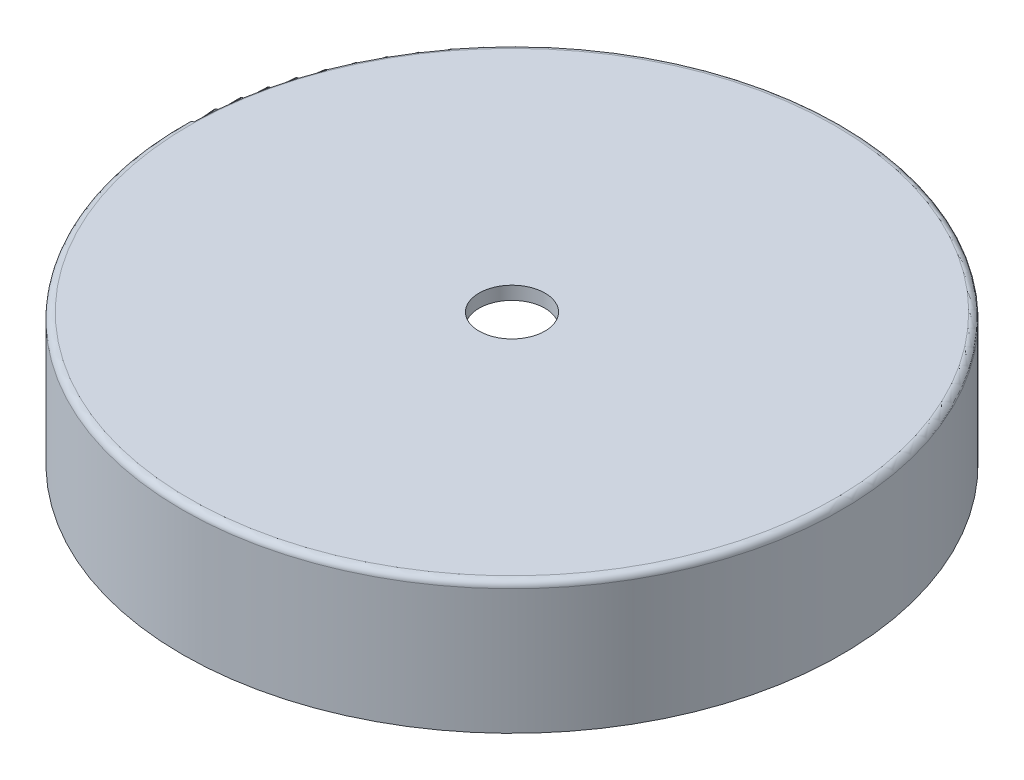
SolidWorks part; units mm, degrees
ref_plane "Plan de face" through (0, 0, 0) normal (0, 0, 1) x (1, 0, 0)
ref_plane "Plan de dessus" through (0, 0, 0) normal (0, 1, 0) x (1, 0, 0)
ref_plane "Plan de droite" through (0, 0, 0) normal (1, 0, 0) x (0, 0, -1)
sketch "Esquisse1" plane through (0, 0, 0) normal (1, 0, 0) x (0, 0, -1)
  line L0 (0, 0) -> (0, 10) construction
  line L1 (0, 10) -> (-25, 10)
  line L2 (-25, 10) -> (-25, 0)
  line L3 (-25, 0) -> (-22, 0)
  line L4 (-22, 0) -> (-22, 9)
  line L5 (-22, 9) -> (0, 9)
  line L6 (0, 10) -> (0, 9)
  dimension "D1" = 3
  dimension "D2" = 25
  dimension "D3" = 1
  dimension "D4" = 10
revolve "Révolution1" add sketch "Esquisse1" angle 360 about L0
fillet "Congé1" radius 0.5 2 edges at (0, 9, -22) (0, 10, -25)
sketch "Esquisse2" plane through (0, 10, 0) normal (0, 1, 0) x (1, 0, 0)
  circle A0 centre (0, 0) radius 2.5
  dimension "D1" = 5
extrude "Enlèv. mat.-Extru.1" cut sketch "Esquisse2" against normal blind 10
